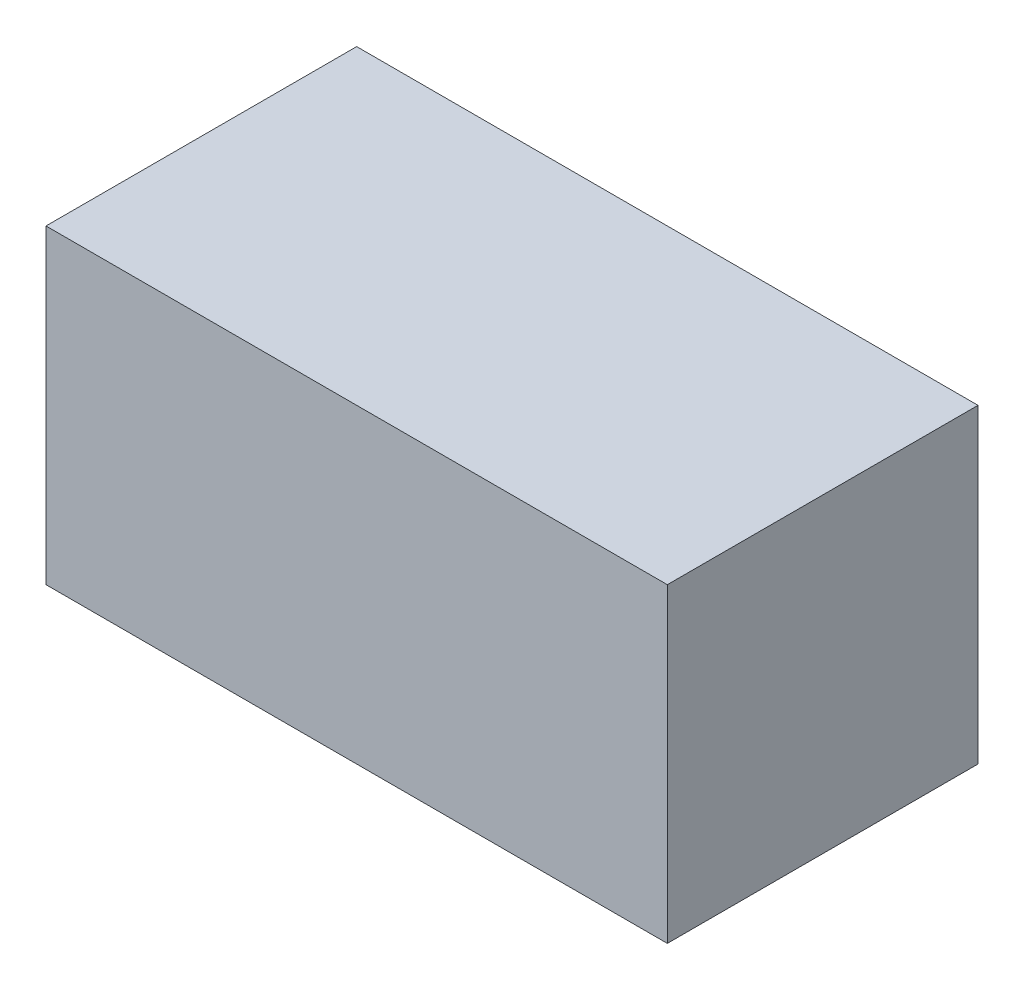
SolidWorks part; units mm, degrees
ref_plane "前视基准面" through (0, 0, 0) normal (0, 0, 1) x (1, 0, 0)
ref_plane "上视基准面" through (0, 0, 0) normal (0, 1, 0) x (1, 0, 0)
ref_plane "右视基准面" through (0, 0, 0) normal (1, 0, 0) x (0, 0, -1)
sketch "草图1" plane through (0, 0, 0) normal (1, 0, 0) x (0, 0, -1)
  line L1 (-2, -2) -> (2, -2)
  line L2 (-2, -2) -> (-2, 2)
  line L3 (-2, 2) -> (2, 2)
  line L4 (2, -2) -> (2, 2)
  line L5 (-2, -2) -> (2, 2) construction
  line L6 (-2, 2) -> (2, -2) construction
  point P0 (0, 0)
  dimension "D1" = 4
extrude "凸台-拉伸1" add sketch "草图1" along normal mid plane 8 contours L3 L4 L1 L2
